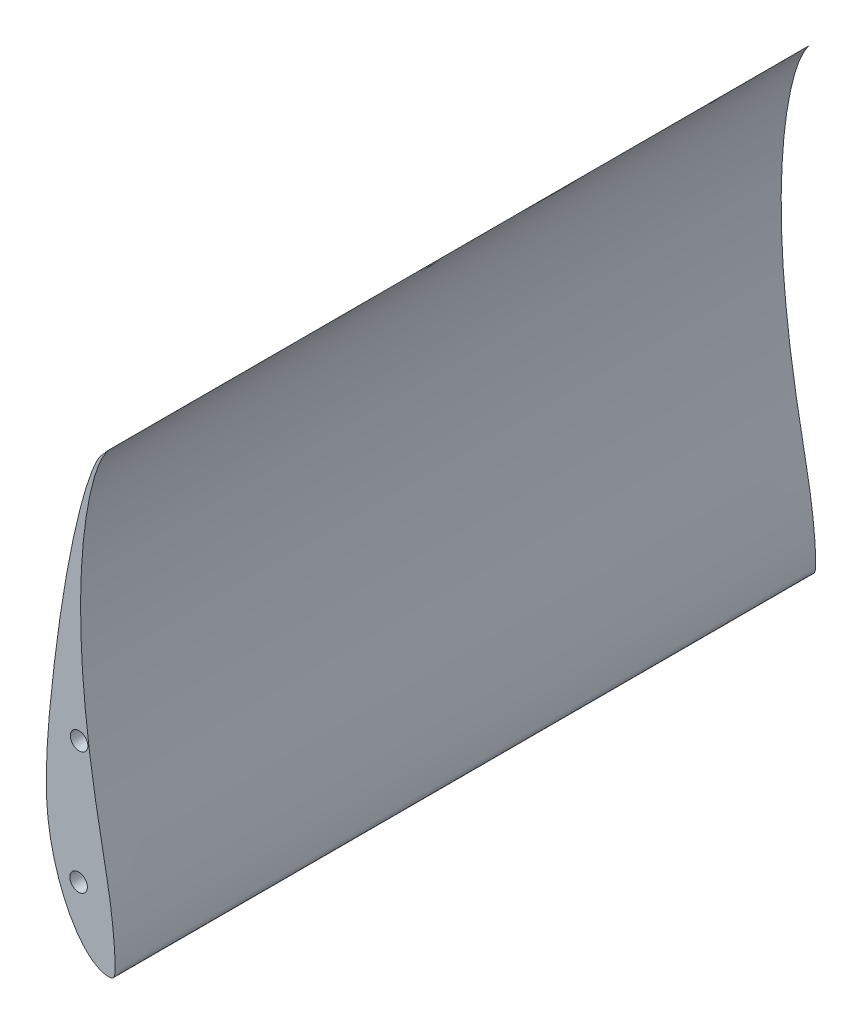
SolidWorks part; units mm, degrees
ref_plane "Front Plane" through (0, 0, 0) normal (0, 0, 1) x (1, 0, 0)
ref_plane "Top Plane" through (0, 0, 0) normal (0, 1, 0) x (1, 0, 0)
ref_plane "Right Plane" through (0, 0, 0) normal (1, 0, 0) x (0, 0, -1)
sketch "Sketch1" plane through (0, 0, 0) normal (0, 0, 1) x (1, 0, 0)
  circle A0 centre (-1.223, -91.8556) radius 5
  circle A1 centre (-0.9311, -21.8556) radius 5
  spline S0 degree 3 poles (14.8427, 128.9064) (15.6857, 130.1482) (14.8744, 129.0594) (14.1652, 128.3365) (12.6838, 126.7315) (11.1079, 124.8379) (9.5192, 122.2477) (7.9795, 119.0268) (6.3728, 115.1383) (4.7212, 110.5883) (3.0365, 105.3979) (1.3333, 99.5942) (-0.3804, 93.2095) (-2.0889, 86.2792) (-3.7797, 78.843) (-5.4424, 70.9452) (-7.0684, 62.6341) (-8.6376, 53.9581) (-10.1479, 44.972) (-11.5798, 35.7276) (-12.9361, 26.2845) (-14.206, 16.7034) (-15.3855, 7.0536) (-16.4829, -2.5877) (-17.4705, -12.1407) (-18.3299, -21.5275) (-19.0127, -30.6823) (-19.4823, -39.5526) (-19.6852, -48.0891) (-19.6636, -56.2481) (-19.2641, -64.0144) (-18.4545, -71.391) (-17.3098, -78.4078) (-15.8269, -85.0667) (-14.0879, -91.3607) (-12.1237, -97.2632) (-9.9802, -102.7492) (-7.6689, -107.7845) (-5.2368, -112.3529) (-2.7114, -116.4297) (-0.127, -119.9893) (2.4616, -123.0302) (5.0826, -125.5082) (7.7135, -127.4117) (10.2729, -128.8177) (12.703, -129.7188) (14.946, -130.1482) (16.843, -130.0653) (18.5829, -129.5769) (19.4466, -127.7615) (19.5677, -125.3206) (19.6852, -121.9815) (19.5041, -117.7823) (19.1713, -112.7705) (18.6383, -107.0019) (17.9171, -100.5356) (16.9923, -93.4029) (15.6997, -85.6075) (14.0787, -77.1113) (12.3147, -67.8719) (10.452, -57.9345) (8.5682, -47.3614) (6.7339, -36.2304) (5.0102, -24.6277) (3.4605, -12.6534) (2.1299, -0.4152) (1.0782, 11.9714) (0.3326, 24.382) (-0.0773, 36.6871) (-0.1291, 48.753) (0.1808, 60.4452) (0.845, 71.6298) (1.8551, 82.1723) (3.1722, 91.9472) (4.7581, 100.8272) (6.5597, 108.7082) (8.4875, 115.445) (10.5451, 120.9584) (12.428, 124.8921) (14.169, 127.7922) (14.8427, 128.9064) (15.6857, 130.1482) (14.8744, 129.0594) knots -0.009748 -0.004147 -0.001 0 0.00098 0.003649 0.007483 0.012095 0.017526 0.024052 0.031783 0.040678 0.05071 0.061833 0.073989 0.087118 0.101145 0.115991 0.13157 0.147788 0.164551 0.181758 0.199312 0.217095 0.23499 0.252857 0.270541 0.287887 0.304773 0.321101 0.336806 0.3518 0.366031 0.379616 0.392653 0.40517 0.417172 0.428604 0.439419 0.449597 0.459102 0.467908 0.475988 0.483309 0.489875 0.495803 0.501149 0.505903 0.510047 0.513579 0.516447 0.51935 0.523823 0.529974 0.537716 0.546968 0.557637 0.56962 0.582804 0.597247 0.613135 0.630444 0.649056 0.668822 0.689595 0.71119 0.733427 0.756094 0.778989 0.80189 0.824567 0.846792 0.868338 0.888978 0.908492 0.926659 0.943286 0.958169 0.971136 0.981956 0.990252 0.995853 0.999 1 1.00098 1.003649 1.007483 only from (15.5179, 129.9125) to (15.5179, 129.9125)
  dimension "D2" = 10
  dimension "D3" = 10
  dimension "D1" = 70
extrude "Boss-Extrude1" add sketch "Sketch1" along normal blind 400
